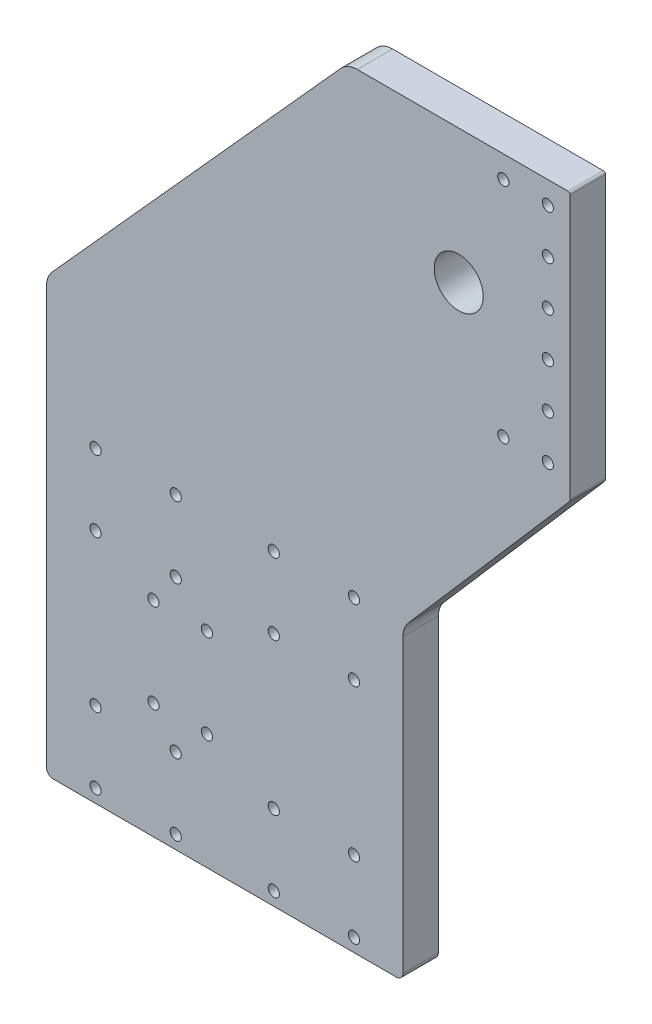
SolidWorks part; units mm, degrees
ref_plane "Front Plane" through (0, 0, 0) normal (0, 0, 1) x (1, 0, 0)
ref_plane "Top Plane" through (0, 0, 0) normal (0, 1, 0) x (1, 0, 0)
ref_plane "Right Plane" through (0, 0, 0) normal (1, 0, 0) x (0, 0, -1)
sketch "Sketch1" plane through (0, 0, 0) normal (0, 0, 1) x (1, 0, 0)
  line L0 (-80, 0) -> (80, 0) construction
  line L1 (-80, 72) -> (80, 72)
  line L2 (-80, 72) -> (-80, -72)
  line L3 (-80, -72) -> (80, -72)
  line L4 (80, 72) -> (80, -72)
  line L5 (-80, 72) -> (80, -72) construction
  line L6 (-80, -72) -> (80, 72) construction
  line L7 (0, 72) -> (0, -72) construction
  circle A0 centre (-58, -66) radius 2.5
  circle A1 centre (-22, -66) radius 2.5
  circle A2 centre (-58, -34) radius 2.5
  circle A3 centre (-22, -34) radius 2.5
  circle A4 centre (58, -66) radius 2.5
  circle A5 centre (22, -66) radius 2.5
  circle A6 centre (22, -34) radius 2.5
  circle A7 centre (58, -34) radius 2.5
  circle A8 centre (-58, 66) radius 2.5
  circle A9 centre (-22, 66) radius 2.5
  circle A10 centre (22, 66) radius 2.5
  circle A11 centre (58, 66) radius 2.5
  circle A12 centre (58, 34) radius 2.5
  circle A13 centre (22, 34) radius 2.5
  circle A14 centre (-22, 34) radius 2.5
  circle A15 centre (-58, 34) radius 2.5
  point P0 (0, 0)
  dimension "D3" = 5
  dimension "D4" = 5
  dimension "D5" = 5
  dimension "D6" = 5
  dimension "D7" = 36
  dimension "D8" = 32
  dimension "D9" = 80
  dimension "D10" = 100
  dimension "D1" = 144
  dimension "D2" = 160
extrude "Boss-Extrude1" add sketch "Sketch1" along normal blind 15.875
sketch "Sketch2" plane through (0, 0, 15.875) normal (0, 0, 1) x (1, 0, 0)
  line L1 (55, 272) -> (155, 272)
  line L2 (155, 272) -> (155, 152)
  line L3 (155, 152) -> (80, 152)
  line L4 (80, 152) -> (80, 72)
  line L5 (80, 72) -> (-80, 72)
  line L6 (-80, 72) -> (-80, 122)
  line L7 (-80, 122) -> (55, 272)
  dimension "D1" = 75
  dimension "D2" = 120
  dimension "D3" = 200
  dimension "D4" = 100
  dimension "D5" = 50
extrude "Boss-Extrude2" add sketch "Sketch2" against normal through all
sketch "Sketch3" plane through (0, 0, 15.875) normal (0, 0, 1) x (1, 0, 0)
  line L0 (155, 152) -> (80, 65.5898)
  line L1 (80, -72) -> (80, 152) construction
  line L2 (80, 65.5898) -> (80, 152)
  line L3 (80, 152) -> (155, 152)
  line L6 (80, -72) -> (80, 152) construction
extrude "Boss-Extrude3" add sketch "Sketch3" against normal through all
fillet "Fillet2" radius 10 3 edges at (80, 65.5898, 7.9375) (-80, 122, 7.9375) (55, 272, 7.9375)
sketch "Sketch4" plane through (0, 0, 15.875) normal (0, 0, 1) x (1, 0, 0)
  line L0 (-20, 0) -> (-20, 33.2415) construction
  line L1 (-20, 33.2415) -> (-20, 0) construction
  line L2 (-20, 0) -> (-46.4387, 0) construction
  circle A0 centre (-32, 20) radius 2.5
  circle A1 centre (-8, 20) radius 2.5
  circle A2 centre (-8, -20) radius 2.5
  circle A3 centre (-32, -20) radius 2.5
  dimension "D3" = 5
  dimension "D1" = 20
  dimension "D2" = 12
  dimension "D4" = 20
extrude "Cut-Extrude1" cut sketch "Sketch4" against normal through all
fillet "Fillet3" radius 1 1 edges at (155, 272, 7.9375)
sketch "Sketch5" plane through (0, 0, 15.875) normal (0, 0, 1) x (1, 0, 0)
  line L0 (145, 120.8838) -> (145, 262) construction
  line L1 (145, 262) -> (23.5289, 262) construction
  line L2 (154, 272) -> (59.4536, 272) construction
  line L3 (155, 152) -> (155, 271) construction
  circle A0 centre (145, 262) radius 2.5
  circle A1 centre (145, 242) radius 2.5
  circle A2 centre (145, 222) radius 2.5
  circle A3 centre (145, 202) radius 2.5
  circle A4 centre (145, 182) radius 2.5
  circle A5 centre (145, 162) radius 2.5
  circle A6 centre (125, 162) radius 2.5
  circle A7 centre (125, 262) radius 2.5
  dimension "D3" = 5
  dimension "D1" = 10
  dimension "D2" = 10
  dimension "D4" = 6
  dimension "D5" = 2
extrude "Cut-Extrude2" cut sketch "Sketch5" against normal through all
fillet "Fillet4" radius 2 1 edges at (155, 152, 7.9375)
sketch "Sketch6" plane through (0, 0, 15.875) normal (0, 0, 1) x (1, 0, 0)
  line L0 (145, 222) -> (145, 202) construction
  line L1 (145, 202) -> (145, 212) construction
  line L2 (145, 212) -> (65, 212) construction
  line L3 (81.5, 212) -> (81.5, 235.5) construction
  circle A0 centre (105, 212) radius 11
  circle A1 centre (145, 222) radius 2.5 construction
  point P9 (105, 212)
  point P23 (80, 172)
  dimension "D1" = 22
  dimension "D2" = 40
  dimension "D3" = 23.5
  dimension "D4" = 23.5
extrude "Cut-Extrude3" cut sketch "Sketch6" against normal through all
fillet "Fillet5" radius 3 2 edges at (80, -72, 7.9375) (-80, -72, 7.9375)
